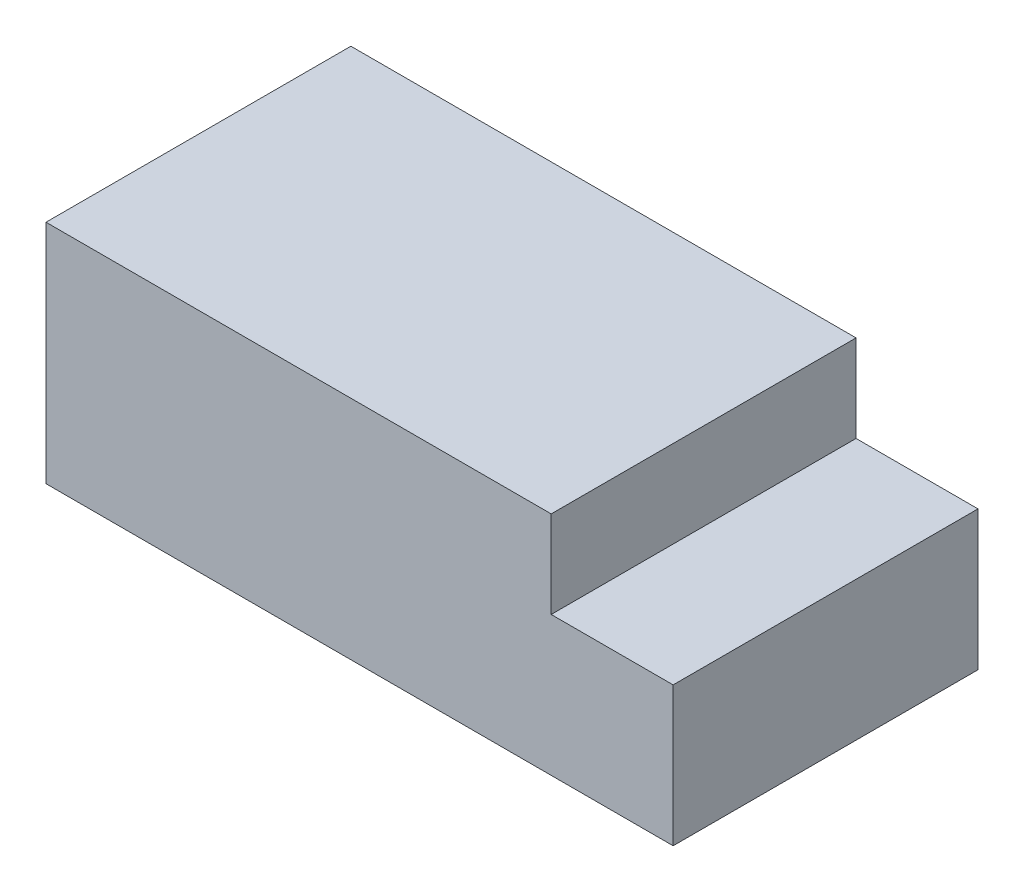
SolidWorks part; units mm, degrees
material "PA Type 6"
ref_plane "Front Plane" through (0, 0, 0) normal (0, 0, 1) x (1, 0, 0)
ref_plane "Top Plane" through (0, 0, 0) normal (0, 1, 0) x (1, 0, 0)
ref_plane "Right Plane" through (0, 0, 0) normal (1, 0, 0) x (0, 0, -1)
sketch "Sketch1" plane through (0, 0, 0) normal (0, 1, 0) x (1, 0, 0)
  line L1 (-14.5, -8.75) -> (14.5, -8.75)
  line L2 (-14.5, -8.75) -> (-14.5, 8.75)
  line L3 (-14.5, 8.75) -> (14.5, 8.75)
  line L4 (14.5, -8.75) -> (14.5, 8.75)
  line L5 (-14.5, -8.75) -> (14.5, 8.75) construction
  line L6 (-14.5, 8.75) -> (14.5, -8.75) construction
  point P0 (0, 0)
  dimension "D1" = 17.5
  dimension "D2" = 29
extrude "Boss-Extrude1" add sketch "Sketch1" along normal mid plane 13
sketch "Sketch2" plane through (14.5, 0, 0) normal (1, 0, 0) x (0, 0, -1)
  line L1 (-8.75, -6.5) -> (8.75, -6.5)
  line L2 (-8.75, -6.5) -> (-8.75, 1.5)
  line L3 (-8.75, 1.5) -> (8.75, 1.5)
  line L4 (8.75, -6.5) -> (8.75, 1.5)
  line L5 (8.75, 6.5) -> (8.75, -6.5) construction
  dimension "D1" = 8
extrude "Boss-Extrude2" add sketch "Sketch2" along normal blind 7
